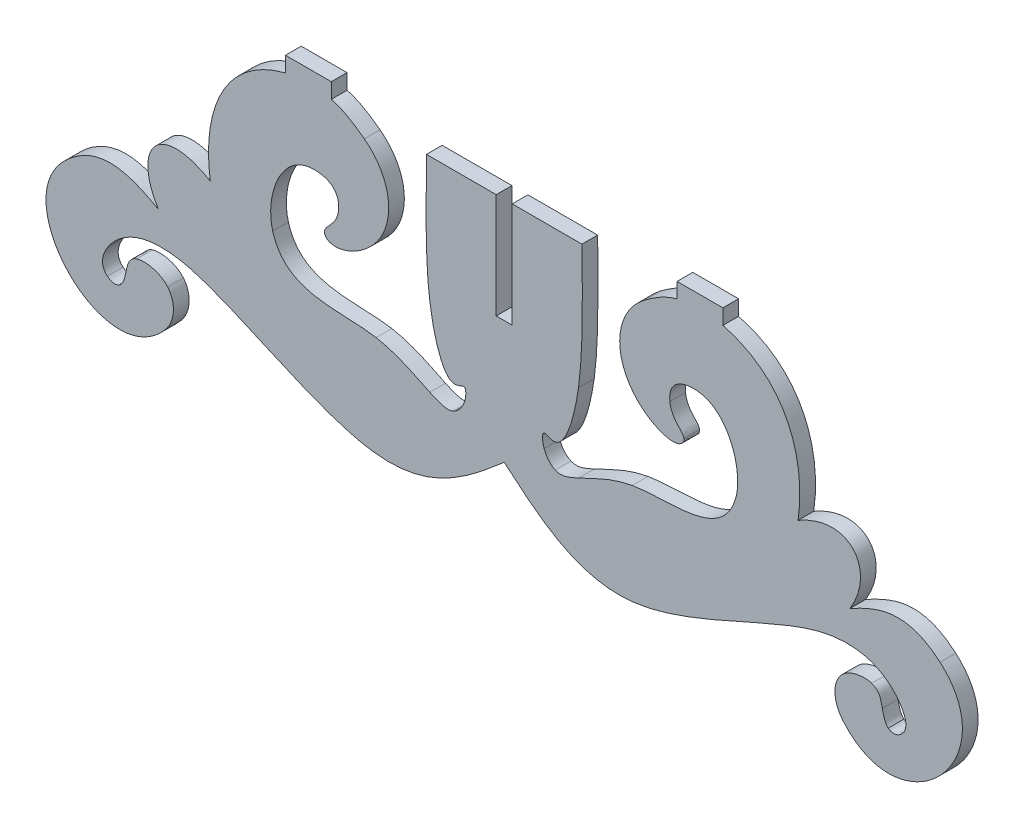
SolidWorks part; units mm, degrees
ref_plane "Plano frontal" through (0, 0, 0) normal (0, 0, 1) x (1, 0, 0)
ref_plane "Plano superior" through (0, 0, 0) normal (0, 1, 0) x (1, 0, 0)
ref_plane "Plano direito" through (0, 0, 0) normal (1, 0, 0) x (0, 0, -1)
sketch "Model" plane through (0, 0, 0) normal (0, 0, 1) x (1, 0, 0)
  line L16 (2.6823, 130.0541) -> (-2.1377, 130.0541)
  line L17 (-2.1377, 130.0541) -> (-2.1377, 128.1173)
  line L18 (-2.1377, 128.1173) -> (-6.2057, 128.1173)
  line L19 (-18.3132, 128.1252) -> (-18.3132, 130.0761)
  line L20 (-18.3132, 130.0761) -> (-24.1465, 130.0761)
  line L21 (-24.1465, 130.0761) -> (-24.1465, 128.1252)
  line L22 (31.5377, 128.1252) -> (31.5377, 130.0651)
  line L23 (31.5377, 130.0651) -> (25.7044, 130.0651)
  line L24 (25.7044, 130.0651) -> (25.7044, 128.1252)
  line L25 (13.5969, 128.1173) -> (9.529, 128.1173)
  line L26 (9.529, 128.1173) -> (9.529, 130.0541)
  line L27 (9.529, 130.0541) -> (4.7156, 130.0541)
  line L28 (4.7156, 130.0541) -> (4.7156, 114.742)
  line L29 (4.7156, 114.742) -> (4.6856, 114.742)
  line L30 (4.6856, 114.742) -> (2.7124, 114.742)
  line L31 (2.7124, 114.742) -> (2.6823, 114.742)
  line L32 (2.6823, 114.742) -> (2.6823, 130.0541)
  line L58 (-2.1377, 128.1173) -> (9.529, 128.1173)
  spline S55 degree 3 poles (-6.2057, 128.1173) (-6.2872, 122.1805) (-6.3375, 116.0426) (-5.7664, 112.0638) knots 0.040541 0.040541 0.040541 0.040541 0.054054 0.054054 0.054054 0.054054
  spline S56 degree 3 poles (-5.7664, 112.0638) (-5.1953, 108.0851) (-4.2478, 105.6627) (-3.3619, 104.8992) knots 0.054054 0.054054 0.054054 0.054054 0.067568 0.067568 0.067568 0.067568
  spline S57 degree 3 poles (-3.3619, 104.8992) (-2.476, 104.1357) (-1.6518, 105.031) (-1.3838, 104.874) knots 0.067568 0.067568 0.067568 0.067568 0.081081 0.081081 0.081081 0.081081
  spline S58 degree 3 poles (-1.3838, 104.874) (-1.1158, 104.7169) (-1.1279, 103.9092) (-1.3936, 103.1749) knots 0.081081 0.081081 0.081081 0.081081 0.094595 0.094595 0.094595 0.094595
  spline S59 degree 3 poles (-1.3936, 103.1749) (-1.6592, 102.4407) (-2.1785, 101.78) (-2.8073, 101.5081) knots 0.094595 0.094595 0.094595 0.094595 0.108108 0.108108 0.108108 0.108108
  spline S60 degree 3 poles (-2.8073, 101.5081) (-3.4361, 101.2363) (-4.1745, 101.3534) (-5.7653, 102.0982) knots 0.108108 0.108108 0.108108 0.108108 0.121622 0.121622 0.121622 0.121622
  spline S61 degree 3 poles (-5.7653, 102.0982) (-7.3562, 102.8428) (-9.7995, 104.2151) (-12.6058, 104.713) knots 0.121622 0.121622 0.121622 0.121622 0.135135 0.135135 0.135135 0.135135
  spline S62 degree 3 poles (-12.6058, 104.713) (-17.1488, 105.519) (-24.0882, 103.9546) (-25.7754, 109.8716) knots 0.135135 0.135135 0.135135 0.135135 0.148649 0.148649 0.148649 0.148649
  spline S63 degree 3 poles (-25.7754, 109.8716) (-26.7745, 113.3756) (-24.8277, 119.1922) (-20.6093, 119.2976) knots 0.148649 0.148649 0.148649 0.148649 0.162162 0.162162 0.162162 0.162162
  spline S64 degree 3 poles (-20.6093, 119.2976) (-18.663, 119.3462) (-17.1862, 118.4764) (-17.3974, 116.3585) knots 0.162162 0.162162 0.162162 0.162162 0.175676 0.175676 0.175676 0.175676
  spline S65 degree 3 poles (-17.3974, 116.3585) (-17.5799, 114.5287) (-19.0634, 113.9716) (-19.1837, 113.1767) knots 0.175676 0.175676 0.175676 0.175676 0.189189 0.189189 0.189189 0.189189
  spline S66 degree 3 poles (-19.1837, 113.1767) (-19.2528, 112.7207) (-18.8323, 112.2229) (-17.9925, 112.158) knots 0.189189 0.189189 0.189189 0.189189 0.202703 0.202703 0.202703 0.202703
  spline S67 degree 3 poles (-17.9925, 112.158) (-17.1526, 112.0932) (-15.8934, 112.4613) (-14.6869, 113.265) knots 0.202703 0.202703 0.202703 0.202703 0.216216 0.216216 0.216216 0.216216
  spline S68 degree 3 poles (-14.6869, 113.265) (-10.0229, 116.3715) (-9.7672, 122.5736) (-14.1156, 125.881) knots 0.216216 0.216216 0.216216 0.216216 0.22973 0.22973 0.22973 0.22973
  spline S69 degree 3 poles (-14.1156, 125.881) (-15.2489, 126.743) (-16.7519, 127.7519) (-18.3132, 128.1252) knots 0.22973 0.22973 0.22973 0.22973 0.243243 0.243243 0.243243 0.243243
  spline S70 degree 3 poles (-24.1465, 128.1252) (-32.0728, 126.0952) (-34.8065, 118.857) (-33.7182, 111.4167) knots 0.283784 0.283784 0.283784 0.283784 0.297297 0.297297 0.297297 0.297297
  spline S71 degree 3 poles (-33.7182, 111.4167) (-40.2193, 115.1974) (-43.7624, 110.6088) (-40.3391, 105.0184) knots 0.297297 0.297297 0.297297 0.297297 0.310811 0.310811 0.310811 0.310811
  spline S72 degree 3 poles (-40.3391, 105.0184) (-43.641, 106.7993) (-47.4419, 108.6172) (-51.8067, 104.8092) knots 0.310811 0.310811 0.310811 0.310811 0.324324 0.324324 0.324324 0.324324
  spline S73 degree 3 poles (-51.8067, 104.8092) (-60.4961, 97.2284) (-47.1112, 83.2416) (-39.4697, 92.1461) knots 0.324324 0.324324 0.324324 0.324324 0.337838 0.337838 0.337838 0.337838
  spline S74 degree 3 poles (-39.4697, 92.1461) (-38.0901, 93.7537) (-38.1508, 95.8393) (-39.1413, 97.0212) knots 0.337838 0.337838 0.337838 0.337838 0.351351 0.351351 0.351351 0.351351
  spline S75 degree 3 poles (-39.1413, 97.0212) (-40.1318, 98.2031) (-42.052, 98.4813) (-43.0896, 98.1476) knots 0.351351 0.351351 0.351351 0.351351 0.364865 0.364865 0.364865 0.364865
  spline S76 degree 3 poles (-43.0896, 98.1476) (-44.1272, 97.814) (-44.2821, 96.8684) (-44.4469, 96.0633) knots 0.364865 0.364865 0.364865 0.364865 0.378378 0.378378 0.378378 0.378378
  spline S77 degree 3 poles (-44.4469, 96.0633) (-44.6116, 95.2582) (-44.7862, 94.5935) (-45.1953, 94.252) knots 0.378378 0.378378 0.378378 0.378378 0.391892 0.391892 0.391892 0.391892
  spline S78 degree 3 poles (-45.1953, 94.252) (-45.6043, 93.9105) (-46.2477, 93.8921) (-46.8277, 94.3876) knots 0.391892 0.391892 0.391892 0.391892 0.405405 0.405405 0.405405 0.405405
  spline S79 degree 3 poles (-46.8277, 94.3876) (-47.4077, 94.8831) (-47.9242, 95.8925) (-46.7036, 97.7025) knots 0.405405 0.405405 0.405405 0.405405 0.418919 0.418919 0.418919 0.418919
  spline S80 degree 3 poles (-46.7036, 97.7025) (-45.4829, 99.5125) (-42.525, 102.1232) (-36.2036, 100.4665) knots 0.418919 0.418919 0.418919 0.418919 0.432432 0.432432 0.432432 0.432432
  spline S81 degree 3 poles (-36.2036, 100.4665) (-29.8822, 98.8098) (-20.1973, 92.8857) (-12.9869, 91.9486) knots 0.432432 0.432432 0.432432 0.432432 0.445946 0.445946 0.445946 0.445946
  spline S82 degree 3 poles (-12.9869, 91.9486) (-5.7764, 91.0116) (-1.0404, 95.0614) (3.6956, 99.1113) knots 0.445946 0.445946 0.445946 0.445946 0.459459 0.459459 0.459459 0.459459
  spline S83 degree 3 poles (3.6956, 99.1113) (8.4316, 95.0614) (13.1676, 91.0116) (20.3781, 91.9486) knots 0.459459 0.459459 0.459459 0.459459 0.472973 0.472973 0.472973 0.472973
  spline S84 degree 3 poles (20.3781, 91.9486) (27.5885, 92.8857) (37.2734, 98.8098) (43.5948, 100.4665) knots 0.472973 0.472973 0.472973 0.472973 0.486486 0.486486 0.486486 0.486486
  spline S85 degree 3 poles (43.5948, 100.4665) (49.9162, 102.1232) (52.8741, 99.5125) (54.0948, 97.7025) knots 0.486486 0.486486 0.486486 0.486486 0.5 0.5 0.5 0.5
  spline S86 degree 3 poles (54.0948, 97.7025) (55.3154, 95.8925) (54.7988, 94.8831) (54.2189, 94.3876) knots 0.5 0.5 0.5 0.5 0.513514 0.513514 0.513514 0.513514
  spline S87 degree 3 poles (54.2189, 94.3876) (53.6389, 93.8921) (52.9955, 93.9105) (52.5865, 94.252) knots 0.513514 0.513514 0.513514 0.513514 0.527027 0.527027 0.527027 0.527027
  spline S88 degree 3 poles (52.5865, 94.252) (52.1774, 94.5935) (52.0028, 95.2582) (51.838, 96.0633) knots 0.527027 0.527027 0.527027 0.527027 0.540541 0.540541 0.540541 0.540541
  spline S89 degree 3 poles (51.838, 96.0633) (51.6733, 96.8684) (51.5184, 97.814) (50.4808, 98.1476) knots 0.540541 0.540541 0.540541 0.540541 0.554054 0.554054 0.554054 0.554054
  spline S90 degree 3 poles (50.4808, 98.1476) (49.4432, 98.4813) (47.5229, 98.2031) (46.5324, 97.0212) knots 0.554054 0.554054 0.554054 0.554054 0.567568 0.567568 0.567568 0.567568
  spline S91 degree 3 poles (46.5324, 97.0212) (45.5419, 95.8393) (45.4813, 93.7537) (46.8609, 92.1461) knots 0.567568 0.567568 0.567568 0.567568 0.581081 0.581081 0.581081 0.581081
  spline S92 degree 3 poles (46.8609, 92.1461) (54.5024, 83.2416) (67.8873, 97.2284) (59.1979, 104.8092) knots 0.581081 0.581081 0.581081 0.581081 0.594595 0.594595 0.594595 0.594595
  spline S93 degree 3 poles (59.1979, 104.8092) (54.8331, 108.6172) (51.0322, 106.7993) (47.7303, 105.0184) knots 0.594595 0.594595 0.594595 0.594595 0.608108 0.608108 0.608108 0.608108
  spline S94 degree 3 poles (47.7303, 105.0184) (51.1536, 110.6088) (47.6105, 115.1974) (41.1094, 111.4167) knots 0.608108 0.608108 0.608108 0.608108 0.621622 0.621622 0.621622 0.621622
  spline S95 degree 3 poles (41.1094, 111.4167) (42.1976, 118.857) (39.464, 126.0952) (31.5377, 128.1252) knots 0.621622 0.621622 0.621622 0.621622 0.635135 0.635135 0.635135 0.635135
  spline S96 degree 3 poles (25.7044, 128.1252) (24.143, 127.7519) (22.6401, 126.743) (21.5068, 125.881) knots 0.675676 0.675676 0.675676 0.675676 0.689189 0.689189 0.689189 0.689189
  spline S97 degree 3 poles (21.5068, 125.881) (17.1584, 122.5736) (17.4141, 116.3715) (22.078, 113.265) knots 0.689189 0.689189 0.689189 0.689189 0.702703 0.702703 0.702703 0.702703
  spline S98 degree 3 poles (22.078, 113.265) (23.2846, 112.4613) (24.5438, 112.0932) (25.3837, 112.158) knots 0.702703 0.702703 0.702703 0.702703 0.716216 0.716216 0.716216 0.716216
  spline S99 degree 3 poles (25.3837, 112.158) (26.2235, 112.2229) (26.6439, 112.7207) (26.5749, 113.1767) knots 0.716216 0.716216 0.716216 0.716216 0.72973 0.72973 0.72973 0.72973
  spline S100 degree 3 poles (26.5749, 113.1767) (26.4546, 113.9716) (24.9711, 114.5287) (24.7886, 116.3585) knots 0.72973 0.72973 0.72973 0.72973 0.743243 0.743243 0.743243 0.743243
  spline S101 degree 3 poles (24.7886, 116.3585) (24.5774, 118.4764) (26.0542, 119.3462) (28.0005, 119.2976) knots 0.743243 0.743243 0.743243 0.743243 0.756757 0.756757 0.756757 0.756757
  spline S102 degree 3 poles (28.0005, 119.2976) (32.2189, 119.1922) (34.1657, 113.3756) (33.1666, 109.8716) knots 0.756757 0.756757 0.756757 0.756757 0.77027 0.77027 0.77027 0.77027
  spline S103 degree 3 poles (33.1666, 109.8716) (31.4794, 103.9546) (24.54, 105.519) (19.9969, 104.713) knots 0.77027 0.77027 0.77027 0.77027 0.783784 0.783784 0.783784 0.783784
  spline S104 degree 3 poles (19.9969, 104.713) (17.1907, 104.2151) (14.7474, 102.8428) (13.1565, 102.0982) knots 0.783784 0.783784 0.783784 0.783784 0.797297 0.797297 0.797297 0.797297
  spline S105 degree 3 poles (13.1565, 102.0982) (11.5657, 101.3534) (10.8273, 101.2363) (10.1985, 101.5081) knots 0.797297 0.797297 0.797297 0.797297 0.810811 0.810811 0.810811 0.810811
  spline S106 degree 3 poles (10.1985, 101.5081) (9.5697, 101.78) (9.0504, 102.4407) (8.7847, 103.1749) knots 0.810811 0.810811 0.810811 0.810811 0.824324 0.824324 0.824324 0.824324
  spline S107 degree 3 poles (8.7847, 103.1749) (8.5191, 103.9092) (8.507, 104.7169) (8.775, 104.874) knots 0.824324 0.824324 0.824324 0.824324 0.837838 0.837838 0.837838 0.837838
  spline S108 degree 3 poles (8.775, 104.874) (9.043, 105.031) (9.8672, 104.1357) (10.7531, 104.8992) knots 0.837838 0.837838 0.837838 0.837838 0.851351 0.851351 0.851351 0.851351
  spline S109 degree 3 poles (10.7531, 104.8992) (11.639, 105.6627) (12.5865, 108.0851) (13.1576, 112.0638) knots 0.851351 0.851351 0.851351 0.851351 0.864865 0.864865 0.864865 0.864865
  spline S110 degree 3 poles (13.1576, 112.0638) (13.7287, 116.0426) (13.6784, 122.1805) (13.5969, 128.1173) knots 0.864865 0.864865 0.864865 0.864865 0.878378 0.878378 0.878378 0.878378
extrude "Ressalto-extrusão3" add sketch "Model" along normal blind 2 contours S109 S110 L25 L26 L27 L28 L29 L30 L31 L32 L16 L17 L18 S55 S56 S57 S58 S59 S60 S61 S62 S63 S64 S65 S66 S67 S68 S69 L19 L20 L21 S70 S71 S72 S73 S74 S75 S76 S77 S78 S79 S80 S81 S82 S83 S84 S85 S86 S87 S88 S89
